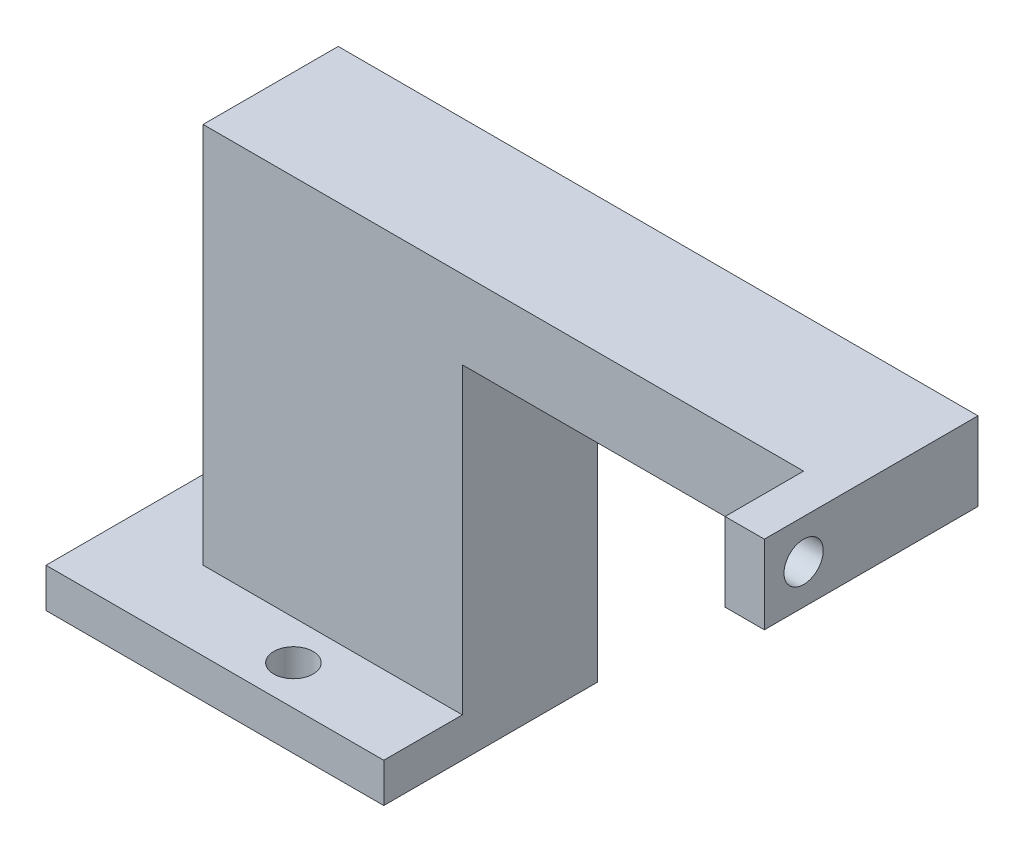
SolidWorks part; units mm, degrees
ref_plane "Ebene vorne" through (0, 0, 0) normal (0, 0, 1) x (1, 0, 0)
ref_plane "Ebene oben" through (0, 0, 0) normal (0, 1, 0) x (1, 0, 0)
ref_plane "Ebene rechts" through (0, 0, 0) normal (1, 0, 0) x (0, 0, -1)
sketch "Skizze1" plane through (0, 0, 0) normal (0, 1, 0) x (1, 0, 0)
  line L1 (-22.77, 7.8375) -> (10.23, 7.8375)
  line L2 (-22.77, 7.8375) -> (-22.77, -9.3625)
  line L3 (-22.77, -9.3625) -> (10.23, -9.3625)
  line L4 (10.23, 7.8375) -> (10.23, -9.3625)
  dimension "D1" = 33
  dimension "D2" = 17.2
extrude "Aufsatz-Linear austragen1" add sketch "Skizze1" along normal blind 53.6
sketch "Skizze2" plane through (10.23, 0, 0) normal (1, 0, 0) x (0, 0, -1)
  line L0 (7.8375, 53.6) -> (7.8375, 0) construction
  line L1 (-9.3625, 53.6) -> (7.8375, 53.6)
  line L2 (-9.3625, 53.6) -> (-9.3625, 43.6)
  line L3 (-9.3625, 43.6) -> (7.8375, 43.6)
  line L4 (7.8375, 53.6) -> (7.8375, 43.6)
  dimension "D1" = 10
extrude "Aufsatz-Linear austragen2" add sketch "Skizze2" along normal blind 48.45
sketch "Skizze3" plane through (0, 0, 9.3625) normal (0, 0, 1) x (1, 0, 0)
  line L0 (10.23, 43.6) -> (10.23, 0) construction
  line L1 (-22.77, 0) -> (10.23, 0)
  line L2 (-22.77, 0) -> (-22.77, 5)
  line L3 (-22.77, 5) -> (10.23, 5)
  line L4 (10.23, 0) -> (10.23, 5)
  line L5 (58.68, 43.6) -> (10.23, 43.6) construction
  line L6 (58.68, 53.6) -> (53.68, 53.6)
  line L7 (58.68, 53.6) -> (58.68, 43.6)
  line L8 (58.68, 43.6) -> (53.68, 43.6)
  line L9 (53.68, 53.6) -> (53.68, 43.6)
  dimension "D1" = 5
  dimension "D2" = 5
extrude "Aufsatz-Linear austragen3" add sketch "Skizze3" along normal blind 10
sketch "Skizze4" plane through (-22.77, 0, 0) normal (-1, 0, 0) x (0, 0, 1)
  line L1 (19.3625, 5) -> (-7.8375, 5)
  line L2 (19.3625, 5) -> (19.3625, 0)
  line L3 (19.3625, 0) -> (-7.8375, 0)
  line L4 (-7.8375, 5) -> (-7.8375, 0)
extrude "Aufsatz-Linear austragen4" add sketch "Skizze4" along normal blind 10
sketch "Skizze5" plane through (53.68, 0, 0) normal (-1, 0, 0) x (0, 0, 1)
  circle A0 centre (14.3625, 48.6) radius 2.5
extrude "Schnitt-Linear austragen1" cut sketch "Skizze5" against normal blind 10
sketch "Skizze6" plane through (0, 5, 0) normal (0, 1, 0) x (1, 0, 0)
  circle A0 centre (-27.77, 0) radius 2.5
  circle A1 centre (-6.27, -14.3625) radius 2.5
extrude "Schnitt-Linear austragen2" cut sketch "Skizze6" against normal blind 10
